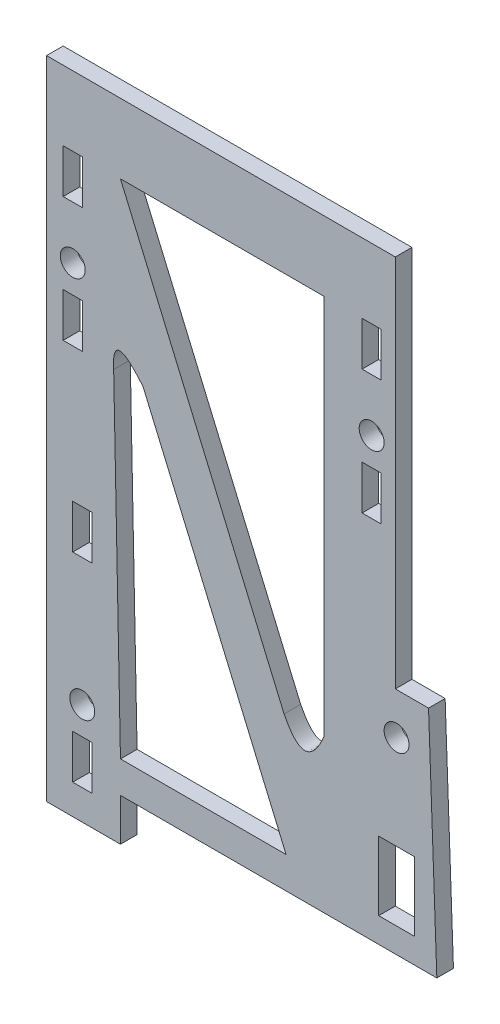
SolidWorks part; units mm, degrees
ref_plane "前视基准面" through (0, 0, 0) normal (0, 0, 1) x (1, 0, 0)
ref_plane "上视基准面" through (0, 0, 0) normal (0, 1, 0) x (1, 0, 0)
ref_plane "右视基准面" through (0, 0, 0) normal (1, 0, 0) x (0, 0, -1)
sketch "草图1" plane through (0, 0, 0) normal (0, 0, 1) x (1, 0, 0)
  line L1 (-13.1829, -11.201) -> (-15.1829, -6.201) construction
  line L2 (-15.1829, -6.201) -> (-13.1829, -4.201) construction
  line L3 (-13.1829, -4.201) -> (-15.1829, -1.201) construction
  line L4 (-15.1829, -1.201) -> (-13.1829, 3.799) construction
  line L5 (-13.1829, 3.799) -> (-15.1829, 8.799) construction
  line L6 (24.6671, 17.3485) -> (24.6671, -27.7015)
  line L7 (-17.3329, 17.3485) -> (24.6671, 17.3485)
  line L8 (20.6671, 8.949) -> (16.0671, 8.949) construction
  line L9 (20.6671, 3.799) -> (20.6671, 3.649) construction
  line L10 (20.8171, 3.799) -> (20.6671, 3.799) construction
  line L11 (22.8171, 8.949) -> (22.9671, 8.949) construction
  line L12 (22.8171, 8.799) -> (22.8171, 8.949) construction
  line L13 (20.8171, 3.799) -> (22.8171, 8.799) construction
  line L14 (-15.1829, -11.201) -> (-13.1829, -11.201) construction
  line L15 (-15.1829, -6.201) -> (-15.1829, -6.051) construction
  line L16 (-15.1829, -6.051) -> (-15.3329, -6.051) construction
  line L17 (-13.1829, -11.201) -> (-13.0329, -11.201) construction
  line L18 (-13.0329, -11.201) -> (-13.0329, -11.351) construction
  line L19 (-13.1829, 3.799) -> (-15.1829, 8.799) construction
  line L20 (-15.3329, -6.051) -> (-13.0329, -6.051)
  line L21 (-15.3329, -6.051) -> (-15.3329, -11.351)
  line L22 (-15.3329, -11.351) -> (-13.0329, -11.351)
  line L23 (-13.0329, -6.051) -> (-13.0329, -11.351)
  line L24 (-15.1829, 8.799) -> (-15.1829, 8.949) construction
  line L25 (-15.1829, 8.949) -> (-15.3329, 8.949) construction
  line L26 (-13.1829, 3.799) -> (-13.0329, 3.799) construction
  line L27 (-13.0329, 3.799) -> (-13.0329, 3.649) construction
  line L28 (-15.3329, 8.949) -> (-13.0329, 8.949)
  line L29 (-15.3329, 8.949) -> (-15.3329, 3.649)
  line L30 (-15.3329, 3.649) -> (-13.0329, 3.649)
  line L31 (-13.0329, 8.949) -> (-13.0329, 3.649)
  line L33 (20.6671, -11.201) -> (20.6671, -11.351) construction
  line L34 (20.8171, -11.201) -> (20.6671, -11.201) construction
  line L35 (22.8171, -6.051) -> (22.9671, -6.051) construction
  line L36 (22.8171, -6.201) -> (22.8171, -6.051) construction
  line L37 (22.8171, -11.201) -> (20.8171, -11.201) construction
  line L38 (20.8171, 3.799) -> (22.8171, 8.799) construction
  line L39 (22.8171, -1.201) -> (20.8171, 3.799) construction
  line L40 (20.8171, -4.201) -> (22.8171, -1.201) construction
  line L41 (22.8171, -6.201) -> (20.8171, -4.201) construction
  line L42 (20.8171, -11.201) -> (22.8171, -6.201) construction
  line L47 (22.8171, -11.201) -> (20.8171, -7.201) construction
  line L71 (24.8171, -32.7015) -> (24.8171, -44.2015) construction
  line L72 (20.6671, 8.949) -> (20.6671, 3.649)
  line L77 (22.9671, 3.649) -> (20.6671, 3.649)
  line L78 (22.9671, 8.949) -> (22.9671, 3.649)
  line L79 (-17.3329, -11.6515) -> (-17.3329, -14.6515)
  line L82 (22.9671, 8.949) -> (20.6671, 8.949)
  line L84 (-17.3329, -11.6515) -> (-17.3329, 17.3485)
  line L85 (20.6671, -6.051) -> (20.6671, -11.351)
  line L86 (22.9671, -11.351) -> (20.6671, -11.351)
  line L87 (22.9671, -6.051) -> (22.9671, -11.351)
  line L88 (22.9671, -6.051) -> (20.6671, -6.051)
  line L89 (24.8171, -44.2015) -> (24.8171, -48.2015)
  line L92 (26.9671, -52.3515) -> (22.6671, -52.3515)
  line L93 (26.9671, -52.3515) -> (26.9671, -44.0515)
  line L94 (26.9671, -44.0515) -> (22.6671, -44.0515)
  line L95 (22.6671, -52.3515) -> (22.6671, -44.0515)
  line L96 (26.9671, -52.3515) -> (22.6671, -44.0515) construction
  line L97 (26.9671, -44.0515) -> (22.6671, -52.3515) construction
  line L104 (-8.4329, 8.949) -> (16.0671, 8.949)
  line L120 (26.6671, -27.7015) -> (28.6671, -27.7015)
  line L122 (24.6671, -27.7015) -> (26.6671, -27.7015)
  line L123 (22.6671, -55.3515) -> (20.6671, -55.3515)
  line L128 (29.6671, -55.3515) -> (22.6671, -55.3515)
  line L130 (26.9671, -52.3515) -> (62.9671, -52.3515) construction
  line L132 (28.6671, -27.7015) -> (29.6671, -55.3515)
  line L137 (-8.4329, -51.5515) -> (-9.2511, -11.351)
  line L138 (11.2696, -50.9799) -> (-5.719, -11.351)
  line L146 (24.8171, -48.2015) -> (-13.0329, -48.2015) construction
  line L147 (-12.0329, -56.7015) -> (-14.0329, -51.7015) construction
  line L148 (-14.0329, -51.7015) -> (-12.0329, -49.7015) construction
  line L149 (-12.0329, -49.7015) -> (-14.0329, -46.7015) construction
  line L150 (-8.4329, 8.949) -> (11.2696, -37.0107)
  line L151 (-12.0329, -32.7015) -> (-14.0329, -27.7015) construction
  line L152 (-14.0329, -56.7015) -> (-12.0329, -56.7015) construction
  line L153 (-14.0329, -51.7015) -> (-14.0329, -51.5515) construction
  line L154 (-14.0329, -51.5515) -> (-14.1829, -51.5515) construction
  line L155 (-12.0329, -56.7015) -> (-11.8829, -56.7015) construction
  line L156 (-11.8829, -56.7015) -> (-11.8829, -56.8515) construction
  line L157 (-12.0329, -32.7015) -> (-14.0329, -27.7015) construction
  line L158 (-14.1829, -51.5515) -> (-11.8829, -51.5515)
  line L159 (-14.1829, -51.5515) -> (-14.1829, -56.8515)
  line L160 (-14.1829, -56.8515) -> (-11.8829, -56.8515)
  line L161 (-11.8829, -51.5515) -> (-11.8829, -56.8515)
  line L162 (-14.0329, -27.7015) -> (-14.0329, -27.5515) construction
  line L163 (-14.0329, -27.5515) -> (-14.1829, -27.5515) construction
  line L164 (-12.0329, -32.7015) -> (-11.8829, -32.7015) construction
  line L165 (-11.8829, -32.7015) -> (-11.8829, -32.8515) construction
  line L166 (-14.1829, -27.5515) -> (-11.8829, -27.5515)
  line L167 (-14.1829, -27.5515) -> (-14.1829, -32.8515)
  line L168 (-14.1829, -32.8515) -> (-11.8829, -32.8515)
  line L169 (-11.8829, -27.5515) -> (-11.8829, -32.8515)
  line L170 (20.6671, -55.3515) -> (-8.4329, -55.3515)
  line L171 (-8.4329, -55.3515) -> (-8.4329, -60.4515)
  line L172 (-8.4329, -60.4515) -> (-17.3329, -60.4515)
  line L173 (-17.3329, -60.4515) -> (-17.3329, -14.6515)
  line L174 (16.0671, 8.949) -> (16.0671, -48.2015) construction
  line L175 (16.0671, -48.2015) -> (-8.4329, 8.949) construction
  line L176 (-9.4272, -2.701) -> (-8.4329, -51.5515) construction
  line L177 (-9.4272, -2.701) -> (11.2696, -50.9799) construction
  line L178 (-8.4329, -51.5515) -> (11.5147, -51.5515)
  line L179 (11.2696, -50.9799) -> (11.5147, -51.5515)
  line L180 (16.0671, 8.949) -> (16.0671, -37.0107)
  circle A0 centre (-14.1829, -2.701) radius 1.5
  circle A5 centre (21.8171, -2.701) radius 1.5
  circle A7 centre (24.8171, -32.7015) radius 1.5
  circle A8 centre (-13.0329, -48.2015) radius 1.5
  spline S0 degree 2 poles (-5.719, -11.351) (-9.5413, -6.7161) (-9.2511, -11.351) knots 0 0 0 1 1 1
  spline S1 degree 2 poles (11.2696, -37.0107) (13.8524, -42.1441) (16.0671, -37.0107) knots 0 0 0 1 1 1
extrude "凸台-拉伸1" add sketch "草图1" along normal blind 2
